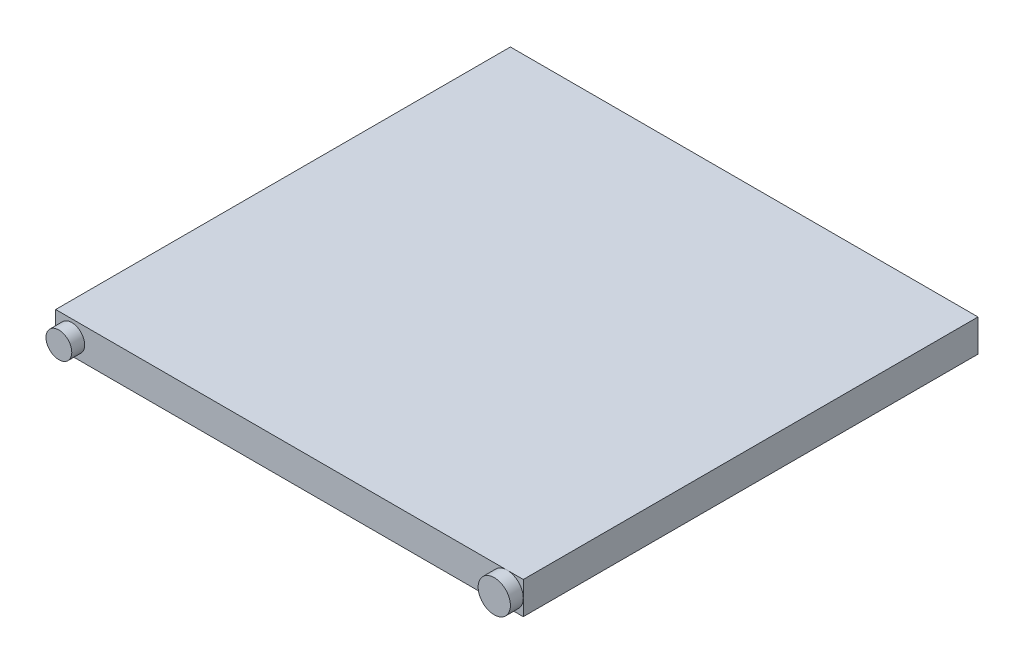
SolidWorks part; units mm, degrees
ref_plane "Front Plane" through (0, 0, 0) normal (0, 0, 1) x (1, 0, 0)
ref_plane "Top Plane" through (0, 0, 0) normal (0, 1, 0) x (1, 0, 0)
ref_plane "Right Plane" through (0, 0, 0) normal (1, 0, 0) x (0, 0, -1)
sketch "Sketch1" plane through (0, 0, 0) normal (0, 1, 0) x (1, 0, 0)
  line L1 (0, 0) -> (145, 0)
  line L2 (0, 0) -> (0, 145)
  line L3 (0, 145) -> (145, 145)
  line L4 (145, 0) -> (145, 145)
extrude "Boss-Extrude1 (Plate 145x145x10)" add sketch "Sketch1" along normal blind 10 flip side to cut
sketch "Sketch2" plane through (0, 0, 0) normal (0, 1, 0) x (1, 0, 0)
  circle A0 centre (15, 15) radius 5.5
  circle A1 centre (27.778, 15) radius 5.5
  circle A2 centre (40.556, 15) radius 5.5
  circle A3 centre (53.334, 15) radius 5.5
  circle A4 centre (66.112, 15) radius 5.5
  circle A5 centre (78.89, 15) radius 5.5
  circle A6 centre (91.668, 15) radius 5.5
  circle A7 centre (104.446, 15) radius 5.5
  circle A8 centre (117.224, 15) radius 5.5
  circle A9 centre (130.002, 15) radius 5.5
  circle A10 centre (15, 27.778) radius 5.5
  circle A11 centre (27.778, 27.778) radius 5.5
  circle A12 centre (40.556, 27.778) radius 5.5
  circle A13 centre (53.334, 27.778) radius 5.5
  circle A14 centre (66.112, 27.778) radius 5.5
  circle A15 centre (78.89, 27.778) radius 5.5
  circle A16 centre (91.668, 27.778) radius 5.5
  circle A17 centre (104.446, 27.778) radius 5.5
  circle A18 centre (117.224, 27.778) radius 5.5
  circle A19 centre (130.002, 27.778) radius 5.5
  circle A20 centre (15, 40.556) radius 5.5
  circle A21 centre (27.778, 40.556) radius 5.5
  circle A22 centre (40.556, 40.556) radius 5.5
  circle A23 centre (53.334, 40.556) radius 5.5
  circle A24 centre (66.112, 40.556) radius 5.5
  circle A25 centre (78.89, 40.556) radius 5.5
  circle A26 centre (91.668, 40.556) radius 5.5
  circle A27 centre (104.446, 40.556) radius 5.5
  circle A28 centre (117.224, 40.556) radius 5.5
  circle A29 centre (130.002, 40.556) radius 5.5
  circle A30 centre (15, 53.334) radius 5.5
  circle A31 centre (27.778, 53.334) radius 5.5
  circle A32 centre (40.556, 53.334) radius 5.5
  circle A33 centre (53.334, 53.334) radius 5.5
  circle A34 centre (66.112, 53.334) radius 5.5
  circle A35 centre (78.89, 53.334) radius 5.5
  circle A36 centre (91.668, 53.334) radius 5.5
  circle A37 centre (104.446, 53.334) radius 5.5
  circle A38 centre (117.224, 53.334) radius 5.5
  circle A39 centre (130.002, 53.334) radius 5.5
  circle A40 centre (15, 66.112) radius 5.5
  circle A41 centre (27.778, 66.112) radius 5.5
  circle A42 centre (40.556, 66.112) radius 5.5
  circle A43 centre (53.334, 66.112) radius 5.5
  circle A44 centre (66.112, 66.112) radius 5.5
  circle A45 centre (78.89, 66.112) radius 5.5
  circle A46 centre (91.668, 66.112) radius 5.5
  circle A47 centre (104.446, 66.112) radius 5.5
  circle A48 centre (117.224, 66.112) radius 5.5
  circle A49 centre (130.002, 66.112) radius 5.5
  circle A50 centre (15, 78.89) radius 5.5
  circle A51 centre (27.778, 78.89) radius 5.5
  circle A52 centre (40.556, 78.89) radius 5.5
  circle A53 centre (53.334, 78.89) radius 5.5
  circle A54 centre (66.112, 78.89) radius 5.5
  circle A55 centre (78.89, 78.89) radius 5.5
  circle A56 centre (91.668, 78.89) radius 5.5
  circle A57 centre (104.446, 78.89) radius 5.5
  circle A58 centre (117.224, 78.89) radius 5.5
  circle A59 centre (130.002, 78.89) radius 5.5
  circle A60 centre (15, 91.668) radius 5.5
  circle A61 centre (27.778, 91.668) radius 5.5
  circle A62 centre (40.556, 91.668) radius 5.5
  circle A63 centre (53.334, 91.668) radius 5.5
  circle A64 centre (66.112, 91.668) radius 5.5
  circle A65 centre (78.89, 91.668) radius 5.5
  circle A66 centre (91.668, 91.668) radius 5.5
  circle A67 centre (104.446, 91.668) radius 5.5
  circle A68 centre (117.224, 91.668) radius 5.5
  circle A69 centre (130.002, 91.668) radius 5.5
  circle A70 centre (15, 104.446) radius 5.5
  circle A71 centre (27.778, 104.446) radius 5.5
  circle A72 centre (40.556, 104.446) radius 5.5
  circle A73 centre (53.334, 104.446) radius 5.5
  circle A74 centre (66.112, 104.446) radius 5.5
  circle A75 centre (78.89, 104.446) radius 5.5
  circle A76 centre (91.668, 104.446) radius 5.5
  circle A77 centre (104.446, 104.446) radius 5.5
  circle A78 centre (117.224, 104.446) radius 5.5
  circle A79 centre (130.002, 104.446) radius 5.5
  circle A80 centre (15, 117.224) radius 5.5
  circle A81 centre (27.778, 117.224) radius 5.5
  circle A82 centre (40.556, 117.224) radius 5.5
  circle A83 centre (53.334, 117.224) radius 5.5
  circle A84 centre (66.112, 117.224) radius 5.5
  circle A85 centre (78.89, 117.224) radius 5.5
  circle A86 centre (91.668, 117.224) radius 5.5
  circle A87 centre (104.446, 117.224) radius 5.5
  circle A88 centre (117.224, 117.224) radius 5.5
  circle A89 centre (130.002, 117.224) radius 5.5
  circle A90 centre (15, 130.002) radius 5.5
  circle A91 centre (27.778, 130.002) radius 5.5
  circle A92 centre (40.556, 130.002) radius 5.5
  circle A93 centre (53.334, 130.002) radius 5.5
  circle A94 centre (66.112, 130.002) radius 5.5
  circle A95 centre (78.89, 130.002) radius 5.5
  circle A96 centre (91.668, 130.002) radius 5.5
  circle A97 centre (104.446, 130.002) radius 5.5
  circle A98 centre (117.224, 130.002) radius 5.5
  circle A99 centre (130.002, 130.002) radius 5.5
extrude "Cut-Extrude2" cut sketch "Sketch2" along normal blind 3
sketch "Sketch3" plane through (0, 0, 0) normal (0, 1, 0) x (1, 0, 0)
  circle A0 centre (5, 5) radius 2.25
  circle A1 centre (140, 5) radius 2.25
  circle A2 centre (5, 140) radius 2.25
  circle A3 centre (140, 140) radius 2.25
sketch "Sketch4" plane through (0, 0, 0) normal (0, 0, 1) x (1, 0, 0)
  circle A0 centre (5, 5) radius 4
  circle A1 centre (140, 5) radius 5
  circle A2 centre (5, 140) radius 4
  circle A3 centre (140, 140) radius 4
extrude "Cut-Extrude3 (4 Counterbores ร 8 Depth 4mm)" cut sketch "Sketch4" against normal blind 4 flip side to cut
